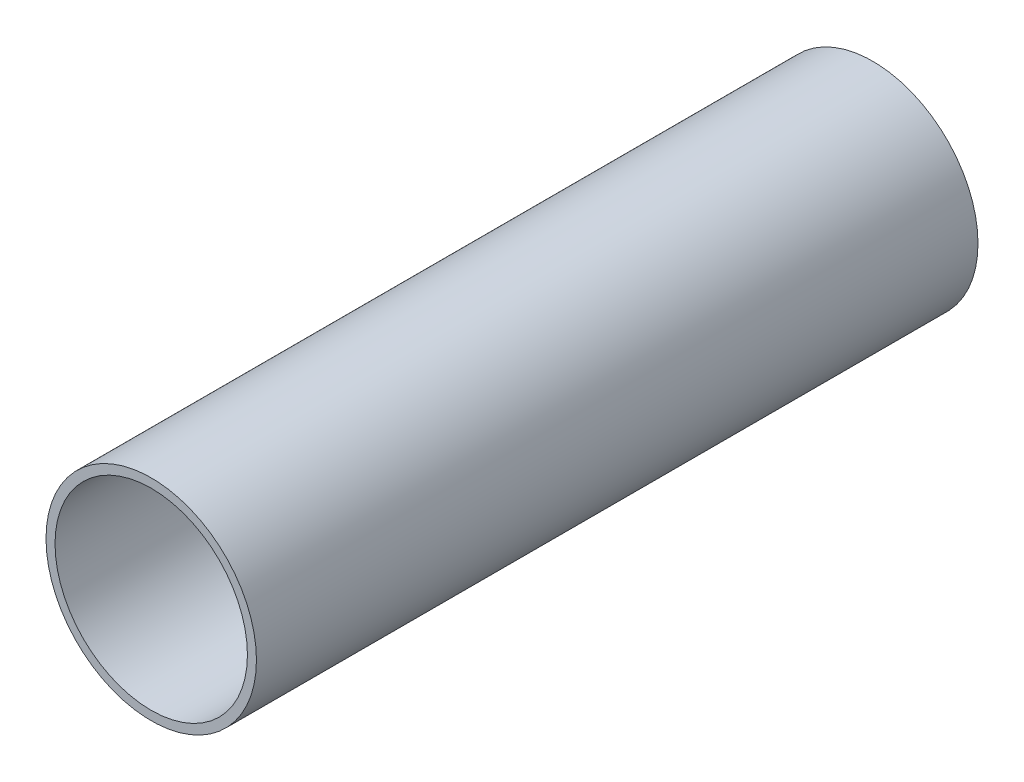
SolidWorks part; units mm, degrees
ref_plane "Спереди" through (0, 0, 0) normal (0, 0, 1) x (1, 0, 0)
ref_plane "Сверху" through (0, 0, 0) normal (0, 1, 0) x (1, 0, 0)
ref_plane "Справа" through (0, 0, 0) normal (1, 0, 0) x (0, 0, -1)
sketch "Эскиз1" plane through (0, 0, 0) normal (0, 0, 1) x (1, 0, 0)
  circle A0 centre (0, 0) radius 8.75
  dimension "D1" = 17.5
extrude "Вытянуть-Тонкостенный1" add sketch "Эскиз1" along normal blind 60 thin thin type one direction reverse wall 0.75
